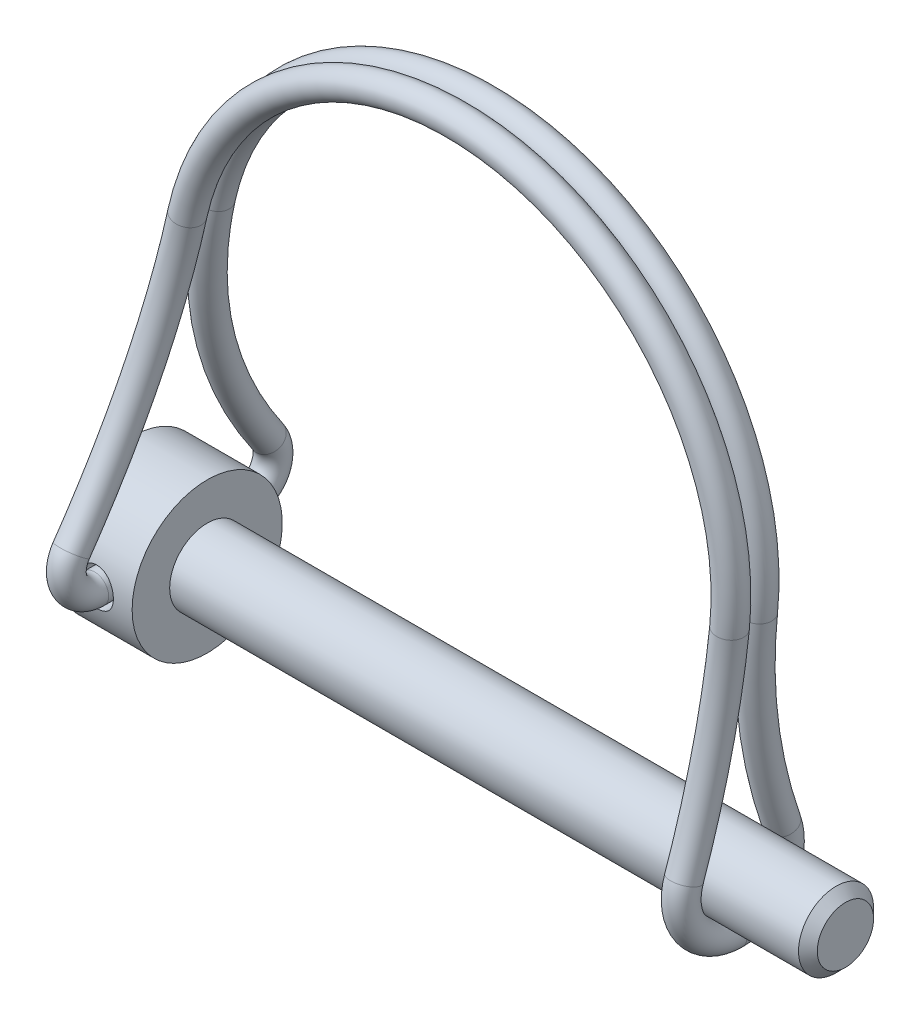
SolidWorks part; units mm, degrees
material "Plain Carbon Steel"
ref_plane "Front Plane" through (0, 0, 0) normal (0, 0, 1) x (1, 0, 0)
ref_plane "Top Plane" through (0, 0, 0) normal (0, 1, 0) x (1, 0, 0)
ref_plane "Right Plane" through (0, 0, 0) normal (1, 0, 0) x (0, 0, -1)
sketch "Sketch1" plane through (0, 0, 0) normal (0, 0, 1) x (1, 0, 0)
  line L0 (0, 0) -> (60.325, 0) construction
  line L1 (0, 0) -> (0, 6.35)
  line L2 (0, 6.35) -> (6.35, 6.35)
  line L3 (6.35, 6.35) -> (6.35, 3.175)
  line L4 (6.35, 3.175) -> (60.325, 3.175)
  line L5 (60.325, 3.175) -> (60.325, 0)
  line L6 (0, 0) -> (60.325, 0)
  dimension "D1" = 6.35
  dimension "D2" = 12.7
  dimension "D3" = 60.325
  dimension "D4" = 6.35
revolve "Revolve1" add sketch "Sketch1" angle 360 about L0
sketch "Sketch2" plane through (0, 0, 0) normal (0, 0, 1) x (1, 0, 0)
  line L0 (3.175, 6.35) -> (3.175, -6.35) construction
  line L1 (6.35, 6.35) -> (0, 6.35) construction
  line L2 (0, -6.35) -> (6.35, -6.35) construction
  circle A0 centre (3.175, 0) radius 1.5875
  dimension "D1" = 3.175
extrude "Cut-Extrude1" cut sketch "Sketch2" against normal through all and the other way through all
chamfer "Chamfer1" distance 0.7937 angle 45 1 edges at (60.325, 0, 3.175)
sketch3d "3DSketch1"
  line L0 (3.175, 0, 0) -> (3.175, 0, 6.35)
  line L1 (6.35, 0, 0) -> (50.8, 0, 0) construction
  line L2 (28.575, 44.4341, 1.1906) -> (28.575, 0, 1.1906) construction
  line L3 (28.575, 0, 0) -> (28.575, 0, 1.1906) construction
  circle A0 centre (6.35, 0, 0) radius 3.175 construction
  circle A1 centre (3.175, 0, 0) radius 1.1906 construction
  arc A2 (50.8, 1.4303, 4.1247) -> (50.8, -4.3656, 0) centre (50.8, 0, 0) ccw
  arc A3 (50.8, 1.4303, 4.1247) -> (51.714, 18.7997, 1.1906) centre (66, 17.334, 49.9861) ccw
  arc A4 (51.714, 18.7997, 1.1906) -> (5.8596, 26.1796, 1.1906) centre (28.575, 21.1736, 1.1906) ccw
  arc A5 (3.175, 0, 6.35) -> (3.175, 3.7569, 8.3133) centre (3.175, 2.3914, 6.35) ccw
  arc A6 (3.175, 3.7569, 8.3133) -> (5.8596, 26.1796, 1.1906) centre (16.7147, 23.7874, 37.1128) ccw
  point P6 (3.175, 0, 0)
  point P8 (3.175, 0, 1.1906)
  point P10 (55.1656, 0, 0)
  point P13 (114.5408, 12.3539, 35.6251)
  point P17 (28.575, 21.1736, 24.4511)
  point P19 (0.7836, 2.3914, 6.35)
  point P22 (51.7951, 16.0564, 25.9973)
  point P23 (28.575, 44.4341, 1.1906)
  point P27 (0, 0, 0)
  dimension "D4" = 2.3813
  dimension "D5" = 4.3656
  dimension "D1" = 6.35
  dimension "D2" = 1.1906
  dimension "D3" = 44.45
  dimension "D6" = 88.9
sketch "Sketch3" plane through (0, 0, 0) normal (0, 0, 1) x (1, 0, 0)
  circle A0 centre (3.175, 0) radius 1.1906
  circle A1 centre (3.175, 0) radius 1.1906 construction
sweep "Sweep1" add profiles "Sketch3" path "3DSketch1"
mirror "Mirror4" about plane through (0, 0, 0) normal (0, 0, 1) of bodies 103
